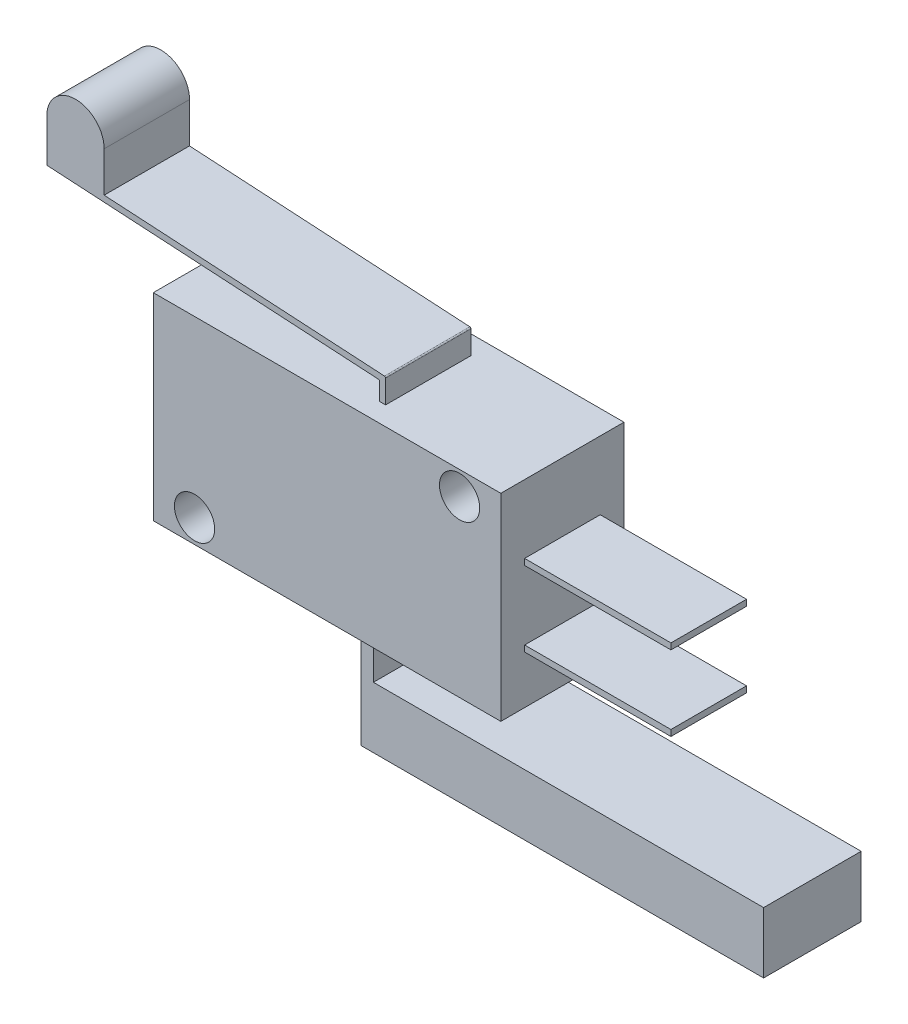
SolidWorks part; units mm, degrees
ref_plane "Plan de face" through (0, 0, 0) normal (0, 0, 1) x (1, 0, 0)
ref_plane "Plan de dessus" through (0, 0, 0) normal (0, 1, 0) x (1, 0, 0)
ref_plane "Plan de droite" through (0, 0, 0) normal (1, 0, 0) x (0, 0, -1)
sketch "Esquisse1" plane through (0, 0, 0) normal (0, 0, 1) x (1, 0, 0)
  line L1 (-14.25, -8.1) -> (14.25, -8.1)
  line L2 (-14.25, -8.1) -> (-14.25, 8.1)
  line L3 (-14.25, 8.1) -> (14.25, 8.1)
  line L4 (14.25, -8.1) -> (14.25, 8.1)
  line L5 (-14.25, -8.1) -> (14.25, 8.1) construction
  line L6 (-14.25, 8.1) -> (14.25, -8.1) construction
  circle A0 centre (-10.8667, -6.1769) radius 1.65
  circle A1 centre (10.8675, 6.1773) radius 1.65
  point P0 (0, 0)
  dimension "D3" = 3.3
  dimension "D1" = 16.2
  dimension "D2" = 28.5
  dimension "D4" = 25
  dimension "D5" = 12.4996
extrude "Boss.-Extru.1" add sketch "Esquisse1" along normal mid plane 10.1
sketch "Esquisse2" plane through (0, 0, 0) normal (0, 0, 1) x (1, 0, 0)
  line L0 (2.75, 8.1) -> (2.75, 9.6285)
  line L1 (14.25, 8.1) -> (-14.25, 8.1) construction
  line L2 (-24.53, 11.2318) -> (2.75, 9.6285)
  line L3 (-24.53, 11.2318) -> (-24.53, 14.75)
  line L4 (-19.83, 14.75) -> (-19.83, 11.4565)
  line L5 (-19.83, 11.4565) -> (3.25, 10.1)
  line L6 (3.25, 10.1) -> (3.25, 8.1)
  line L7 (3.25, 8.1) -> (2.75, 8.1)
  line L8 (14.25, -8.1) -> (14.25, 8.1) construction
  arc A0 (-19.83, 14.75) -> (-24.53, 14.75) centre (-22.18, 14.75) ccw
  dimension "D1" = 4.7
  dimension "D8" = 6
  dimension "D2" = 9
  dimension "D3" = 2
  dimension "D4" = 0.5
  dimension "D5" = 27.78
  dimension "D6" = 0.5
  dimension "D7" = 11
extrude "Boss.-Extru.2" add sketch "Esquisse2" along normal mid plane 7
fillet "Congé1" radius 0.1 2 edges at (3.25, 10.1, 0) (2.75, 9.6285, 0)
sketch "Esquisse3" plane through (14.25, 0, 0) normal (1, 0, 0) x (0, 0, -1)
  line L0 (0, 8.1) -> (0, -8.1) construction
  line L1 (-3.5, 8.1) -> (3.5, 8.1) construction
  line L2 (-5.05, -8.1) -> (5.05, -8.1) construction
  line L3 (-5.05, 8.1) -> (5.05, 8.1) construction
  line L4 (-3.1, 2.5) -> (3.1, 2.5)
  line L5 (-3.1, 2.5) -> (-3.1, 2)
  line L6 (-3.1, 2) -> (3.1, 2)
  line L7 (3.1, 2.5) -> (3.1, 2)
  line L8 (-3.1, 2.5) -> (3.1, 2) construction
  line L9 (-3.1, 2) -> (3.1, 2.5) construction
  line L10 (-3.1, -3.65) -> (3.1, -3.65)
  line L11 (-3.1, -3.65) -> (-3.1, -4.15)
  line L12 (-3.1, -4.15) -> (3.1, -4.15)
  line L13 (3.1, -3.65) -> (3.1, -4.15)
  line L14 (-3.1, -3.65) -> (3.1, -4.15) construction
  line L15 (-3.1, -4.15) -> (3.1, -3.65) construction
  point P6 (0, 2.25)
  point P11 (0, -3.9)
  dimension "D1" = 6.2
  dimension "D2" = 0.5
  dimension "D3" = 5.6
  dimension "D4" = 6.65
extrude "Boss.-Extru.3" add sketch "Esquisse3" along normal blind 12
sketch "Esquisse4" plane through (0, 0, 0) normal (0, 0, 1) x (1, 0, 0)
  line L0 (2.75, -8.1) -> (2.75, -11.6)
  line L1 (-14.25, -8.1) -> (14.25, -8.1) construction
  line L2 (2.75, -11.6) -> (34.75, -11.6)
  line L3 (34.75, -11.6) -> (34.75, -16.6)
  line L4 (34.75, -16.6) -> (1.75, -16.6)
  line L5 (1.75, -16.6) -> (1.75, -8.1)
  line L6 (14.25, -8.1) -> (14.25, 8.1) construction
  line L7 (2.75, -8.1) -> (1.75, -8.1)
  dimension "D1" = 1
  dimension "D2" = 8.5
  dimension "D3" = 3.5
  dimension "D4" = 12.5
  dimension "D5" = 33
extrude "Boss.-Extru.4" add sketch "Esquisse4" along normal mid plane 8
